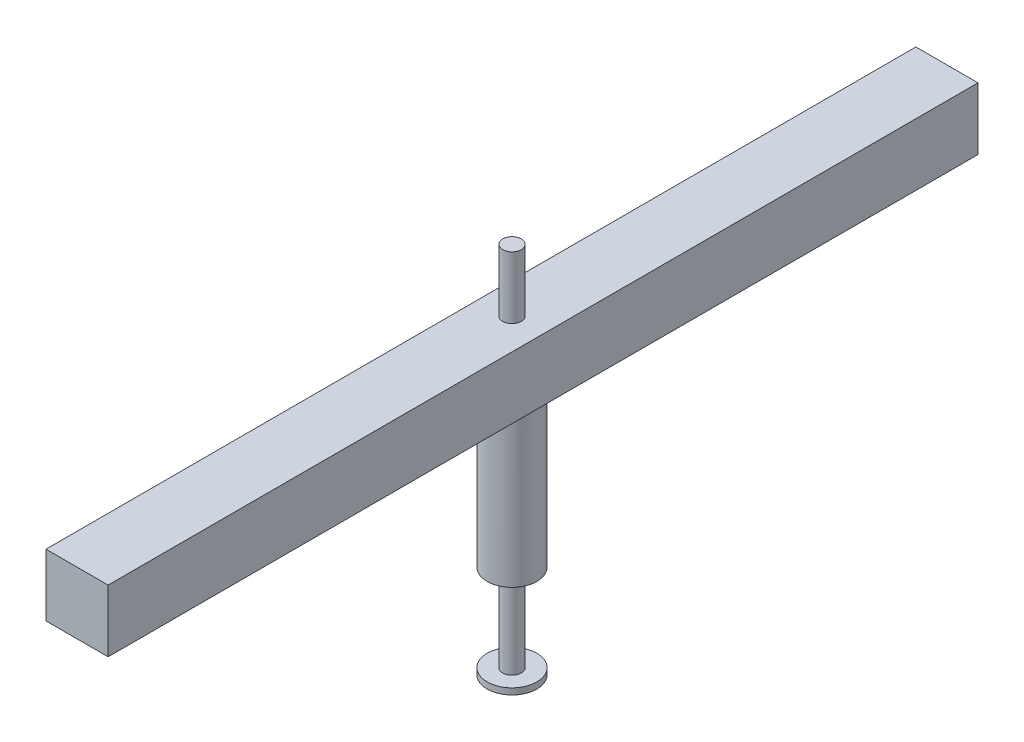
SolidWorks part; units mm, degrees
ref_plane "Front Plane" through (0, 0, 0) normal (0, 0, 1) x (1, 0, 0)
ref_plane "Top Plane" through (0, 0, 0) normal (0, 1, 0) x (1, 0, 0)
ref_plane "Right Plane" through (0, 0, 0) normal (1, 0, 0) x (0, 0, -1)
sketch "Sketch1" plane through (0, 0, 0) normal (0, 0, 1) x (1, 0, 0)
  line L1 (50, -50) -> (-50, -50)
  line L2 (50, -50) -> (50, 50)
  line L3 (50, 50) -> (-50, 50)
  line L4 (-50, -50) -> (-50, 50)
  line L5 (50, -50) -> (-50, 50) construction
  line L6 (50, 50) -> (-50, -50) construction
  point P0 (0, 0)
  dimension "D1" = 100
  dimension "D2" = 100
extrude "Boss-Extrude1" add sketch "Sketch1" along normal blind 1400
sketch "Sketch3" plane through (0, -50, 0) normal (0, -1, 0) x (1, 0, 0)
  line L0 (-50, 700) -> (50, 700) construction
  line L1 (-50, 1400) -> (-50, 0) construction
  line L2 (50, 1400) -> (50, 0) construction
  circle A0 centre (0, 700) radius 15
  dimension "D1" = 30
extrude "Boss-Extrude3" add sketch "Sketch3" along normal blind 400 and the other way blind 200
sketch "Sketch4" plane through (0, -450, 0) normal (0, -1, 0) x (1, 0, 0)
  circle A0 centre (0, 700) radius 40
  dimension "D1" = 80
extrude "Boss-Extrude4" add sketch "Sketch4" against normal blind 10
sketch "Sketch5" plane through (0, -50, 0) normal (0, -1, 0) x (1, 0, 0)
  circle A0 centre (0, 700) radius 40
  dimension "D1" = 80
extrude "Boss-Extrude5" add sketch "Sketch5" along normal blind 250
